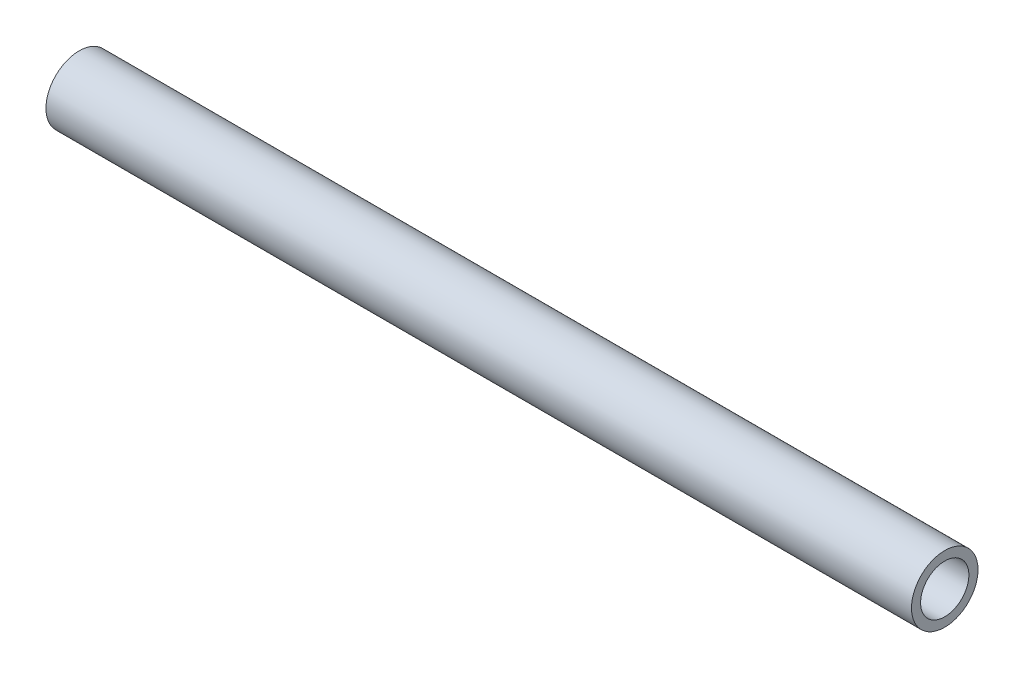
SolidWorks part; units mm, degrees
ref_plane "Front Plane" through (0, 0, 0) normal (0, 0, 1) x (1, 0, 0)
ref_plane "Top Plane" through (0, 0, 0) normal (0, 1, 0) x (1, 0, 0)
ref_plane "Right Plane" through (0, 0, 0) normal (1, 0, 0) x (0, 0, -1)
sketch "Sketch1" plane through (0, 0, 0) normal (1, 0, 0) x (0, 0, -1)
  circle A0 centre (0, 0) radius 13.15
  circle A1 centre (0, 0) radius 9.55
  dimension "D1" = 26.3
  dimension "D2" = 19.1
extrude "Boss-Extrude1" add sketch "Sketch1" along normal blind 342.2
